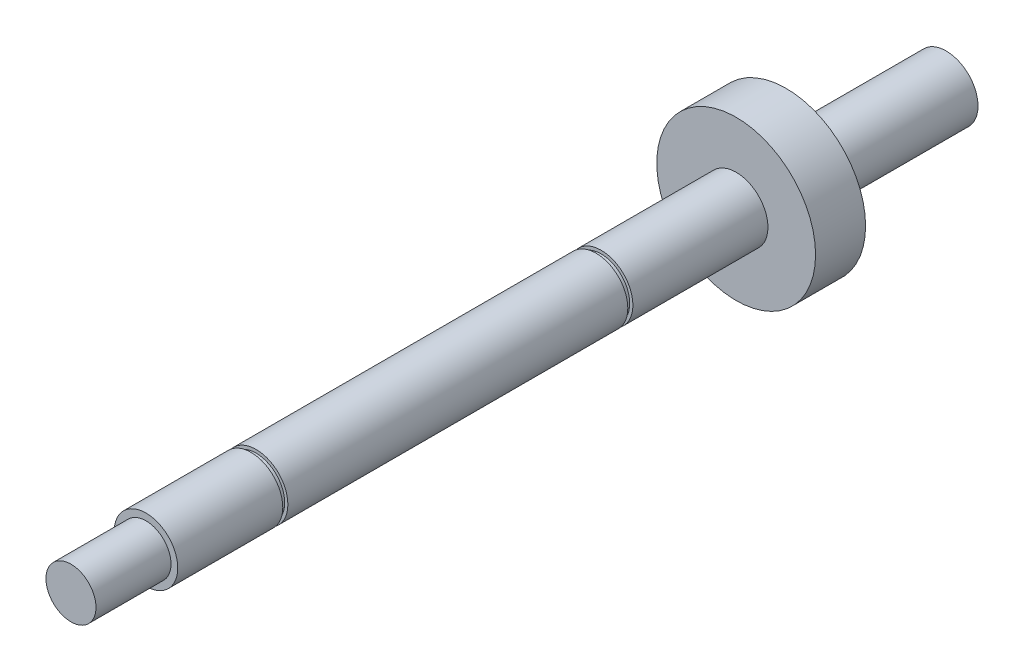
SolidWorks part; units mm, degrees
ref_plane "Front Plane" through (0, 0, 0) normal (0, 0, 1) x (1, 0, 0)
ref_plane "Top Plane" through (0, 0, 0) normal (0, 1, 0) x (1, 0, 0)
ref_plane "Right Plane" through (0, 0, 0) normal (1, 0, 0) x (0, 0, -1)
sketch "Sketch1" plane through (0, 0, 0) normal (0, 0, 1) x (1, 0, 0)
  circle A0 centre (0, 0) radius 6.35
  dimension "D1" = 12.7
extrude "Boss-Extrude1" add sketch "Sketch1" along normal blind 175
sketch "Sketch2" plane through (0, 0, 0) normal (0, 0, 1) x (1, 0, 0)
  circle A0 centre (0, 0) radius 5
  circle A1 centre (0, 0) radius 8.2128
  dimension "D1" = 10
extrude "Cut-Extrude1" cut sketch "Sketch2" against normal blind 15 from surface at 175 starting at face at (6.35, 0, 175)
sketch "Sketch3" plane through (0, 0, 0) normal (0, 0, 1) x (1, 0, 0)
  circle A0 centre (0, 0) radius 15.875
  dimension "D1" = 31.75
extrude "Boss-Extrude2" add sketch "Sketch3" against normal blind 10 from offset 42
sketch "Sketch4" plane through (0, 0, 0) normal (0, 0, 1) x (1, 0, 0)
  circle A0 centre (0, 0) radius 5.715
  circle A1 centre (0, 0) radius 12.7
  dimension "D1" = 11.43
  dimension "D2" = 25.4
extrude "Cut-Extrude2" cut sketch "Sketch4" along normal blind 1.016 from offset 69
sketch "Sketch5" plane through (0, 0, 0) normal (0, 0, 1) x (1, 0, 0)
  circle A0 centre (0, 0) radius 5.715
  circle A1 centre (0, 0) radius 12.7
  dimension "D1" = 11.43
  dimension "D2" = 25.4
extrude "Cut-Extrude3" cut sketch "Sketch5" against normal blind 1.016 from offset 139
